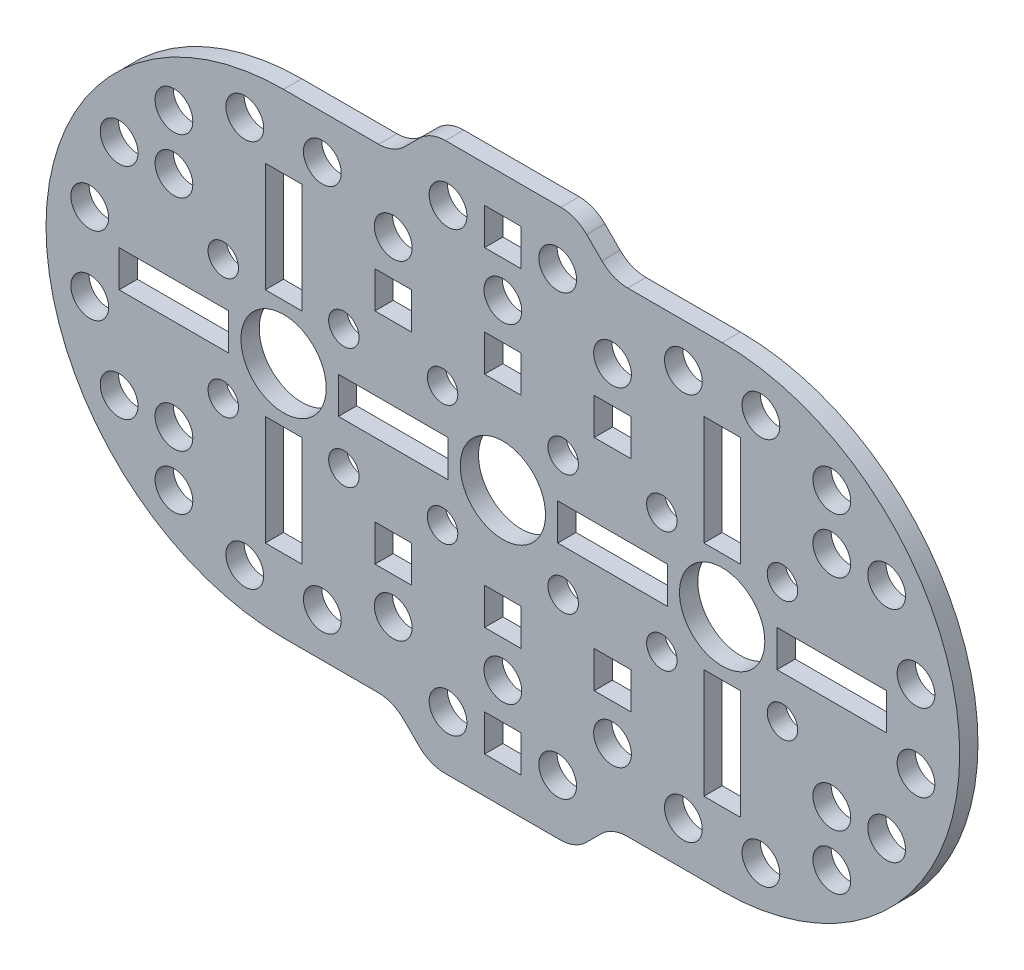
SolidWorks part; units mm, degrees
ref_plane "Alzado" through (0, 0, 0) normal (0, 0, 1) x (1, 0, 0)
ref_plane "Planta" through (0, 0, 0) normal (0, 1, 0) x (1, 0, 0)
ref_plane "Vista lateral" through (0, 0, 0) normal (1, 0, 0) x (0, 0, -1)
sketch "Model" plane through (0, 0, 0) normal (0, 0, 1) x (1, 0, 0)
  line L0 (32.2955, 274.8523) -> (41.2955, 274.8523)
  line L1 (32.2955, 277.8523) -> (32.2955, 274.8523)
  line L2 (41.2955, 277.8523) -> (32.2955, 277.8523)
  line L3 (41.2955, 274.8523) -> (41.2955, 277.8523)
  line L4 (29.2955, 280.8523) -> (29.2955, 289.8523)
  line L5 (26.2955, 280.8523) -> (29.2955, 280.8523)
  line L6 (26.2955, 289.8523) -> (26.2955, 280.8523)
  line L7 (29.2955, 289.8523) -> (26.2955, 289.8523)
  line L8 (23.2955, 277.8523) -> (14.2955, 277.8523)
  line L9 (23.2955, 274.8523) -> (23.2955, 277.8523)
  line L10 (14.2955, 274.8523) -> (23.2955, 274.8523)
  line L11 (14.2955, 277.8523) -> (14.2955, 274.8523)
  line L12 (26.2955, 271.8523) -> (26.2955, 262.8523)
  line L13 (29.2955, 271.8523) -> (26.2955, 271.8523)
  line L14 (29.2955, 262.8523) -> (29.2955, 271.8523)
  line L15 (26.2955, 262.8523) -> (29.2955, 262.8523)
  line L16 (68.2955, 274.8523) -> (77.2955, 274.8523)
  line L17 (68.2955, 277.8523) -> (68.2955, 274.8523)
  line L18 (77.2955, 277.8523) -> (68.2955, 277.8523)
  line L19 (77.2955, 274.8523) -> (77.2955, 277.8523)
  line L20 (65.2955, 280.8523) -> (65.2955, 289.8523)
  line L21 (62.2955, 280.8523) -> (65.2955, 280.8523)
  line L22 (62.2955, 289.8523) -> (62.2955, 280.8523)
  line L23 (65.2955, 289.8523) -> (62.2955, 289.8523)
  line L24 (59.2955, 277.8523) -> (50.2955, 277.8523)
  line L25 (59.2955, 274.8523) -> (59.2955, 277.8523)
  line L26 (50.2955, 274.8523) -> (59.2955, 274.8523)
  line L27 (50.2955, 277.8523) -> (50.2955, 274.8523)
  line L28 (62.2955, 271.8523) -> (62.2955, 262.8523)
  line L29 (65.2955, 271.8523) -> (62.2955, 271.8523)
  line L30 (65.2955, 262.8523) -> (65.2955, 271.8523)
  line L31 (62.2955, 262.8523) -> (65.2955, 262.8523)
  line L32 (35.2955, 286.8523) -> (35.2955, 283.8523)
  line L33 (38.2955, 286.8523) -> (35.2955, 286.8523)
  line L34 (38.2955, 283.8523) -> (38.2955, 286.8523)
  line L35 (35.2955, 283.8523) -> (38.2955, 283.8523)
  line L36 (44.2955, 286.8523) -> (44.2955, 283.8523)
  line L37 (47.2955, 286.8523) -> (44.2955, 286.8523)
  line L38 (47.2955, 283.8523) -> (47.2955, 286.8523)
  line L39 (44.2955, 283.8523) -> (47.2955, 283.8523)
  line L40 (53.2955, 286.8523) -> (53.2955, 283.8523)
  line L41 (56.2955, 286.8523) -> (53.2955, 286.8523)
  line L42 (56.2955, 283.8523) -> (56.2955, 286.8523)
  line L43 (53.2955, 283.8523) -> (56.2955, 283.8523)
  line L44 (35.2955, 268.8523) -> (35.2955, 265.8523)
  line L45 (38.2955, 268.8523) -> (35.2955, 268.8523)
  line L46 (38.2955, 265.8523) -> (38.2955, 268.8523)
  line L47 (35.2955, 265.8523) -> (38.2955, 265.8523)
  line L48 (44.2955, 268.8523) -> (44.2955, 265.8523)
  line L49 (47.2955, 268.8523) -> (44.2955, 268.8523)
  line L50 (47.2955, 265.8523) -> (47.2955, 268.8523)
  line L51 (44.2955, 265.8523) -> (47.2955, 265.8523)
  line L52 (53.2955, 268.8523) -> (53.2955, 265.8523)
  line L53 (56.2955, 268.8523) -> (53.2955, 268.8523)
  line L54 (56.2955, 265.8523) -> (56.2955, 268.8523)
  line L55 (53.2955, 265.8523) -> (56.2955, 265.8523)
  line L56 (44.2955, 295.8523) -> (44.2955, 292.8523)
  line L57 (47.2955, 295.8523) -> (44.2955, 295.8523)
  line L58 (47.2955, 292.8523) -> (47.2955, 295.8523)
  line L59 (44.2955, 292.8523) -> (47.2955, 292.8523)
  line L60 (44.2955, 259.8523) -> (44.2955, 256.8523)
  line L61 (47.2955, 259.8523) -> (44.2955, 259.8523)
  line L62 (47.2955, 256.8523) -> (47.2955, 259.8523)
  line L63 (44.2955, 256.8523) -> (47.2955, 256.8523)
  line L64 (63.7955, 295.8523) -> (56.0382, 295.8523)
  line L65 (63.7955, 256.8523) -> (55.9911, 256.8523)
  line L66 (27.7955, 295.8523) -> (35.5999, 295.8523)
  line L67 (27.7955, 256.8523) -> (35.5529, 256.8523)
  line L68 (53.9169, 296.731) -> (52.6742, 297.9736)
  line L70 (37.7213, 296.731) -> (38.9639, 297.9736)
  line L71 (41.0852, 298.8523) -> (50.5529, 298.8523)
  line L72 (53.8698, 255.9736) -> (52.6272, 254.731)
  line L74 (37.6742, 255.9736) -> (38.9169, 254.731)
  line L75 (41.0382, 253.8523) -> (50.5059, 253.8523)
  circle A0 centre (22.8458, 281.302) radius 1.25
  circle A1 centre (22.8458, 271.4025) radius 1.25
  circle A2 centre (32.7453, 271.4025) radius 1.25
  circle A3 centre (32.7453, 281.302) radius 1.25
  circle A4 centre (27.7955, 276.3523) radius 3.5
  circle A5 centre (18.7955, 289.8523) radius 1.55
  circle A6 centre (18.7955, 262.8523) radius 1.55
  circle A7 centre (36.7955, 289.8523) radius 1.55
  circle A8 centre (36.7955, 262.8523) radius 1.55
  circle A9 centre (14.2955, 267.3523) radius 1.55
  circle A10 centre (14.2955, 285.3523) radius 1.55
  circle A11 centre (30.9775, 292.2622) radius 1.55
  circle A12 centre (24.6136, 260.4424) radius 1.55
  circle A13 centre (30.9775, 260.4424) radius 1.55
  circle A14 centre (24.6136, 292.2622) radius 1.55
  circle A15 centre (11.8856, 279.5343) radius 1.55
  circle A16 centre (11.8856, 273.1703) radius 1.55
  circle A17 centre (58.8458, 281.302) radius 1.25
  circle A18 centre (58.8458, 271.4025) radius 1.25
  circle A19 centre (68.7453, 271.4025) radius 1.25
  circle A20 centre (68.7453, 281.302) radius 1.25
  circle A21 centre (54.7955, 289.8523) radius 1.55
  circle A22 centre (54.7955, 262.8523) radius 1.55
  circle A23 centre (72.7955, 289.8523) radius 1.55
  circle A24 centre (72.7955, 262.8523) radius 1.55
  circle A25 centre (77.2955, 267.3523) radius 1.55
  circle A26 centre (77.2955, 285.3523) radius 1.55
  circle A27 centre (66.9775, 292.2622) radius 1.55
  circle A28 centre (60.6136, 260.4424) radius 1.55
  circle A29 centre (66.9775, 260.4424) radius 1.55
  circle A30 centre (60.6136, 292.2622) radius 1.55
  circle A31 centre (79.7054, 273.1703) radius 1.55
  circle A32 centre (79.7054, 279.5343) radius 1.55
  circle A33 centre (63.7955, 276.3523) radius 3.5
  circle A34 centre (18.7955, 285.3523) radius 1.55
  circle A35 centre (18.7955, 267.3523) radius 1.55
  circle A36 centre (72.7955, 285.3523) radius 1.55
  circle A37 centre (72.7955, 267.3523) radius 1.55
  arc A38 (63.7955, 256.8523) -> (63.7955, 295.8523) centre (63.7955, 276.3523) ccw
  arc A39 (27.7955, 295.8523) -> (27.7955, 256.8523) centre (27.7955, 276.3523) ccw
  circle A40 centre (40.8458, 281.302) radius 1.25
  circle A41 centre (40.8458, 271.4025) radius 1.25
  circle A42 centre (50.7453, 271.4025) radius 1.25
  circle A43 centre (50.7453, 281.302) radius 1.25
  circle A44 centre (45.7955, 276.3523) radius 3.5
  circle A45 centre (41.2955, 294.3523) radius 1.55
  circle A46 centre (50.2955, 294.3523) radius 1.55
  circle A47 centre (45.7955, 289.8523) radius 1.55
  circle A48 centre (41.2955, 258.3523) radius 1.55
  circle A49 centre (50.2955, 258.3523) radius 1.55
  circle A50 centre (45.7955, 262.8523) radius 1.55
  arc A51 (53.9169, 296.731) -> (56.0382, 295.8523) centre (56.0382, 298.8523) ccw
  arc A52 (52.6742, 297.9736) -> (50.5529, 298.8523) centre (50.5529, 295.8523) ccw
  arc A53 (35.5999, 295.8523) -> (37.7213, 296.731) centre (35.5999, 298.8523) ccw
  arc A54 (41.0852, 298.8523) -> (38.9639, 297.9736) centre (41.0852, 295.8523) ccw
  arc A55 (55.9911, 256.8523) -> (53.8698, 255.9736) centre (55.9911, 253.8523) ccw
  arc A56 (50.5059, 253.8523) -> (52.6272, 254.731) centre (50.5059, 256.8523) ccw
  arc A57 (37.6742, 255.9736) -> (35.5529, 256.8523) centre (35.5529, 253.8523) ccw
  arc A58 (38.9169, 254.731) -> (41.0382, 253.8523) centre (41.0382, 256.8523) ccw
extrude "Saliente-Extruir1" add sketch "Model" along normal blind 1.5
